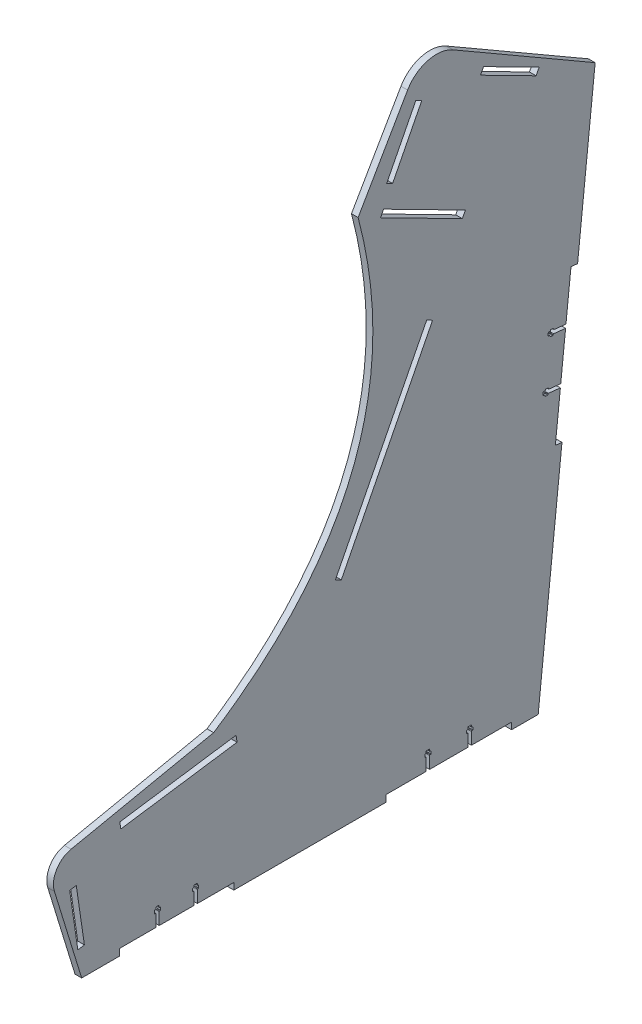
SolidWorks part; units mm, degrees
ref_plane "Front Plane" through (0, 0, 0) normal (0, 0, 1) x (1, 0, 0)
ref_plane "Top Plane" through (0, 0, 0) normal (0, 1, 0) x (1, 0, 0)
ref_plane "Right Plane" through (0, 0, 0) normal (1, 0, 0) x (0, 0, -1)
sketch "Sketch5" plane through (0, 0, 0) normal (1, 0, 0) x (0, 0, -1)
  line L0 (200.2204, 680.0165) -> (997.5537, 680.0165) construction
  line L1 (0, 0) -> (500, 0)
  line L2 (0, 0) -> (0, 800)
  line L3 (0, 800) -> (500, 800)
  line L4 (500, 0) -> (500, 800)
  dimension "D1" = 500
  dimension "D2" = 800
sketch "Sketch6" plane through (0, 0, 0) normal (1, 0, 0) x (0, 0, -1)
  line L0 (443.0084, 0) -> (494.424, 483.6515)
  line L1 (0, 0) -> (500, 0) construction
  line L2 (494.424, 483.6515) -> (366.15, 557.8015)
  line L3 (325.1634, 546.8425) -> (280.507, 469.5903)
  line L5 (150.1347, 132.2032) -> (21.4929, 105.4355)
  line L6 (0, 0) -> (0, 800) construction
  line L7 (6.4499, 79.9789) -> (31.0328, 0)
  line L8 (31.0328, 0) -> (443.0084, 0)
  arc A0 (366.15, 557.8015) -> (325.1634, 546.8425) centre (351.1362, 531.8287) ccw
  arc A1 (21.4929, 105.4355) -> (6.4499, 79.9789) centre (25.5672, 85.8549) ccw
  spline S0 degree 2 poles (280.507, 469.5903) (337.5474, 253.6662) (150.1347, 132.2032) knots 0 0 0 1 1 1
  point P15 (0, 100.9633)
  dimension "D1" = 30
  dimension "D2" = 20
  dimension "D3" = 411.9756
  dimension "D4" = 486.3768
  dimension "D5" = 131.3972
  dimension "D6" = 89.2306
  dimension "D7" = 148.1635
  dimension "D8" = 83.6716
extrude "Boss-Extrude3" add sketch "Sketch6" along normal blind 6
sketch "Sketch7" plane through (6, 0, 0) normal (1, 0, 0) x (0, 0, -1)
  line L0 (27.5611, 23.7476) -> (16.7625, 97.6133)
  line L1 (16.7625, 97.6133) -> (225.0412, 128.062)
  line L2 (225.0412, 128.062) -> (374.5816, 421.6774)
  line L3 (374.5816, 421.6774) -> (295.4085, 462.0008)
  line L4 (295.4085, 462.0008) -> (343.5234, 556.4723)
  line L5 (343.5234, 556.4723) -> (443.8491, 505.3757)
  line L6 (27.5611, 23.7476) -> (33.498, 24.6155)
  line L7 (441.126, 500.0292) -> (346.1469, 548.4027)
  line L8 (346.1469, 548.4027) -> (303.478, 464.6243)
  line L9 (303.478, 464.6243) -> (382.6511, 424.3009)
  line L10 (382.6511, 424.3009) -> (228.9794, 122.574)
  line L11 (228.9794, 122.574) -> (23.5673, 92.5443)
  line L12 (23.5673, 92.5443) -> (33.498, 24.6155)
  line L13 (441.126, 500.0292) -> (443.8491, 505.3757)
  dimension "D1" = 6
  dimension "D2" = 6
  dimension "D3" = 6
  dimension "D4" = 88.8502
  dimension "D5" = 6
  dimension "D6" = 6
  dimension "D7" = 74.6509
  dimension "D8" = 210.4926
  dimension "D9" = 125.307
  dimension "D10" = 6
  dimension "D11" = 106.0184
  dimension "D12" = 112.5881
  dimension "D13" = 335.5032
extrude "Cut-Extrude1" cut sketch "Sketch7" against normal through all
sketch "Sketch9" plane through (6, 0, 0) normal (1, 0, 0) x (0, 0, -1)
  line L0 (16.7625, 97.6133) -> (20.2342, 73.8657)
  line L1 (16.7625, 97.6133) -> (27.5611, 23.7476) construction
  line L2 (20.2342, 73.8657) -> (26.1711, 74.7337)
  line L3 (33.498, 24.6155) -> (23.5673, 92.5443) construction
  line L4 (26.1711, 74.7337) -> (22.6994, 98.4812)
  line L5 (225.0412, 128.062) -> (16.7625, 97.6133) construction
  line L6 (22.6994, 98.4812) -> (16.7625, 97.6133)
  dimension "D1" = 24
extrude "Boss-Extrude10" add sketch "Sketch9" against normal blind 6
sketch "Sketch10" plane through (6, 0, 0) normal (1, 0, 0) x (0, 0, -1)
  line L0 (22.6994, 98.4812) -> (65.4945, 104.7376)
  line L1 (225.0412, 128.062) -> (22.6994, 98.4812) construction
  line L2 (65.4945, 104.7376) -> (66.3624, 98.8007)
  line L3 (23.5673, 92.5443) -> (228.9794, 122.574) construction
  line L4 (66.3624, 98.8007) -> (23.5673, 92.5443)
  line L5 (23.5673, 92.5443) -> (22.6994, 98.4812)
  line L6 (225.0412, 128.062) -> (170.3723, 120.0699)
  line L7 (170.3723, 120.0699) -> (171.2402, 114.133)
  line L8 (171.2402, 114.133) -> (228.9794, 122.574)
  line L9 (228.9794, 122.574) -> (225.0412, 128.062)
  dimension "D1" = 43.25
  dimension "D2" = 55.25
extrude "Boss-Extrude11" add sketch "Sketch10" against normal blind 6
sketch "Sketch11" plane through (6, 0, 0) normal (1, 0, 0) x (0, 0, -1)
  line L0 (382.6511, 424.3009) -> (347.7057, 355.6874)
  line L1 (228.9794, 122.574) -> (382.6511, 424.3009) construction
  line L2 (347.7057, 355.6874) -> (342.3592, 358.4104)
  line L3 (374.5816, 421.6774) -> (225.0412, 128.062) construction
  line L4 (342.3592, 358.4104) -> (377.3046, 427.0239)
  line L5 (382.6511, 424.3009) -> (303.478, 464.6243) construction
  line L6 (377.3046, 427.0239) -> (382.6511, 424.3009)
  line L7 (265.3345, 193.9554) -> (228.9794, 122.574)
  line L8 (228.9794, 122.574) -> (225.0412, 128.062)
  line L9 (225.0412, 128.062) -> (259.988, 196.6784)
  line L10 (259.988, 196.6784) -> (265.3345, 193.9554)
  dimension "D1" = 77
  dimension "D2" = 181.5
extrude "Boss-Extrude12" add sketch "Sketch11" against normal blind 6
sketch "Sketch12" plane through (6, 0, 0) normal (1, 0, 0) x (0, 0, -1)
  line L0 (295.4085, 462.0008) -> (306.3006, 483.3869)
  line L1 (343.5234, 556.4723) -> (295.4085, 462.0008) construction
  line L2 (306.3006, 483.3869) -> (311.6471, 480.6639)
  line L3 (303.478, 464.6243) -> (346.1469, 548.4027) construction
  line L4 (311.6471, 480.6639) -> (300.755, 459.2778)
  line L5 (295.4085, 462.0008) -> (374.5816, 421.6774) construction
  line L6 (300.755, 459.2778) -> (295.4085, 462.0008)
  line L7 (343.5234, 556.4723) -> (332.6314, 535.0862)
  line L8 (332.6314, 535.0862) -> (337.9779, 532.3632)
  line L9 (337.9779, 532.3632) -> (346.1469, 548.4027)
  line L10 (346.1469, 548.4027) -> (390.9685, 525.5748)
  line L11 (346.1469, 548.4027) -> (441.126, 500.0292) construction
  line L12 (390.9685, 525.5748) -> (393.6915, 530.9213)
  line L13 (443.8491, 505.3757) -> (343.5234, 556.4723) construction
  line L14 (393.6915, 530.9213) -> (343.5234, 556.4723)
  dimension "D1" = 24
  dimension "D2" = 24
  dimension "D3" = 56.3
extrude "Boss-Extrude13" add sketch "Sketch12" against normal blind 6
sketch "Sketch13" plane through (6, 0, 0) normal (1, 0, 0) x (0, 0, -1)
  line L0 (0, 0) -> (500, 0) construction
  line L1 (419.0084, 0) -> (305.6784, 0)
  line L2 (419.0084, 0) -> (419.0084, 6)
  line L3 (419.0084, 6) -> (305.6784, 6)
  line L4 (305.6784, 0) -> (305.6784, 6)
  line L6 (65.0217, 0) -> (168.3517, 0)
  line L7 (65.0217, 0) -> (65.0217, 6)
  line L8 (65.0217, 6) -> (168.3517, 6)
  line L9 (168.3517, 0) -> (168.3517, 6)
  dimension "D1" = 6
  dimension "D2" = 6
  dimension "D3" = 113.33
  dimension "D4" = 24
  dimension "D5" = 137.3267
  dimension "D6" = 103.33
  dimension "D7" = 33.9889
extrude "Cut-Extrude2" cut sketch "Sketch13" against normal blind 12
sketch "Sketch15" plane through (6, 0, 0) normal (1, 0, 0) x (0, 0, -1)
  line L0 (464.4724, 201.9057) -> (458.506, 202.54)
  line L1 (443.0084, 0) -> (494.424, 483.6515) construction
  line L2 (458.506, 202.54) -> (472.6009, 335.1263)
  line L3 (472.6009, 335.1263) -> (478.5673, 334.492)
  line L4 (478.5673, 334.492) -> (464.4724, 201.9057)
  dimension "D1" = 6
  dimension "D2" = 133.3333
  dimension "D3" = 150
extrude "Cut-Extrude4" cut sketch "Sketch15" against normal blind 12
sketch "Sketch16" plane through (6, 0, 0) normal (1, 0, 0) x (0, 0, -1)
  line L52 (168.3517, 6) -> (65.0217, 6) construction
  line L53 (97.915, 6) -> (101.015, 6)
  line L54 (97.915, 6) -> (97.915, 22)
  line L55 (97.915, 22) -> (101.015, 22)
  line L56 (101.015, 6) -> (101.015, 22)
  line L57 (65.0217, 6) -> (65.0217, 0) construction
  line L58 (132.3584, 6) -> (135.4584, 6)
  line L59 (132.3584, 6) -> (132.3584, 22)
  line L60 (132.3584, 22) -> (135.4584, 22)
  line L61 (135.4584, 6) -> (135.4584, 22)
  line L62 (168.3517, 0) -> (168.3517, 6) construction
  line L63 (419.0084, 6) -> (305.6784, 6) construction
  line L64 (341.905, 6) -> (345.005, 6)
  line L65 (341.905, 6) -> (341.905, 22)
  line L66 (341.905, 22) -> (345.005, 22)
  line L67 (345.005, 6) -> (345.005, 22)
  line L68 (305.6784, 6) -> (305.6784, 0) construction
  line L69 (379.6817, 6) -> (382.7817, 6)
  line L70 (379.6817, 6) -> (379.6817, 22)
  line L71 (379.6817, 22) -> (382.7817, 22)
  line L72 (382.7817, 6) -> (382.7817, 22)
  line L73 (419.0084, 0) -> (419.0084, 6) construction
  line L74 (463.0403, 245.193) -> (463.368, 248.2756)
  line L75 (472.6009, 335.1263) -> (458.506, 202.54) construction
  line L76 (463.368, 248.2756) -> (447.4577, 249.967)
  line L77 (447.4577, 249.967) -> (447.13, 246.8844)
  line L78 (447.13, 246.8844) -> (463.0403, 245.193)
  line L79 (467.7389, 289.3906) -> (468.0666, 292.4733)
  line L80 (468.0666, 292.4733) -> (452.1562, 294.1646)
  line L81 (452.1562, 294.1646) -> (451.8285, 291.082)
  line L82 (451.8285, 291.082) -> (467.7389, 289.3906)
  line L83 (478.5673, 334.492) -> (472.6009, 335.1263) construction
  line L84 (458.506, 202.54) -> (464.4724, 201.9057) construction
  point P12 (343.455, 6)
  point P15 (381.2317, 6)
  point P38 (99.465, 6)
  point P41 (133.9084, 6)
  point P44 (467.9027, 290.9319)
  point P47 (463.2042, 246.7343)
  dimension "D1" = 3.1
  dimension "D2" = 3.1
  dimension "D3" = 3.1
  dimension "D4" = 3.1
  dimension "D5" = 16
  dimension "D6" = 16
  dimension "D7" = 34.4433
  dimension "D8" = 34.4433
  dimension "D9" = 37.7767
  dimension "D10" = 37.7767
  dimension "D11" = 16
  dimension "D12" = 16
  dimension "D13" = 16
  dimension "D14" = 3.1
  dimension "D15" = 44.4433
  dimension "D16" = 44.4433
extrude "Cut-Extrude5" cut sketch "Sketch16" against normal through all
sketch "Sketch17" plane through (6, 0, 0) normal (1, 0, 0) x (0, 0, -1)
  line L0 (382.7817, 22) -> (379.6817, 22) construction
  line L1 (378.4817, 17.2) -> (383.9817, 17.2)
  line L2 (378.4817, 17.2) -> (378.4817, 20)
  line L3 (378.4817, 20) -> (383.9817, 20)
  line L4 (383.9817, 17.2) -> (383.9817, 20)
  line L5 (345.005, 22) -> (341.905, 22) construction
  line L6 (346.205, 20) -> (340.705, 20)
  line L7 (346.205, 20) -> (346.205, 17.2)
  line L8 (346.205, 17.2) -> (340.705, 17.2)
  line L9 (340.705, 20) -> (340.705, 17.2)
  line L10 (101.015, 22) -> (97.915, 22) construction
  line L11 (136.6584, 20) -> (131.1584, 20)
  line L12 (136.6584, 20) -> (136.6584, 17.2)
  line L13 (136.6584, 17.2) -> (131.1584, 17.2)
  line L14 (131.1584, 20) -> (131.1584, 17.2)
  line L15 (102.215, 20) -> (96.715, 20)
  line L16 (102.215, 20) -> (102.215, 17.2)
  line L17 (102.215, 17.2) -> (96.715, 17.2)
  line L18 (96.715, 20) -> (96.715, 17.2)
  line L19 (135.4584, 22) -> (132.3584, 22) construction
  line L20 (449.5733, 250.9489) -> (452.3576, 250.6529)
  line L21 (452.3576, 250.6529) -> (451.7762, 245.1837)
  line L22 (451.7762, 245.1837) -> (448.9919, 245.4797)
  line L23 (448.9919, 245.4797) -> (449.5733, 250.9489)
  line L24 (463.368, 248.2756) -> (447.4577, 249.967) construction
  line L25 (447.4577, 249.967) -> (447.13, 246.8844) construction
  line L26 (447.13, 246.8844) -> (463.0403, 245.193) construction
  line L27 (454.2719, 295.1465) -> (457.0562, 294.8505)
  line L28 (457.0562, 294.8505) -> (456.4748, 289.3813)
  line L29 (456.4748, 289.3813) -> (453.6904, 289.6773)
  line L30 (453.6904, 289.6773) -> (454.2719, 295.1465)
  line L31 (452.1562, 294.1646) -> (451.8285, 291.082) construction
  line L32 (468.0666, 292.4733) -> (452.1562, 294.1646) construction
  point P6 (381.2317, 20)
  point P7 (381.2317, 22)
  point P14 (343.455, 20)
  point P15 (343.455, 22)
  point P28 (99.465, 20)
  point P29 (99.465, 22)
  point P30 (133.9084, 20)
  point P31 (133.9084, 22)
  dimension "D1" = 2
  dimension "D2" = 2.8
  dimension "D3" = 5.5
  dimension "D4" = 5.5
  dimension "D5" = 2.8
  dimension "D6" = 2
  dimension "D7" = 5.5
  dimension "D8" = 2.8
  dimension "D9" = 2.8
  dimension "D10" = 5.5
  dimension "D11" = 2
  dimension "D12" = 2
  dimension "D13" = 5.5
  dimension "D14" = 2.8
  dimension "D15" = 2
  dimension "D16" = 1.2
  dimension "D17" = 5.5
  dimension "D18" = 2.8
  dimension "D19" = 2
  dimension "D20" = 1.2
extrude "Cut-Extrude6" cut sketch "Sketch17" against normal through all
fillet "Fillet1" radius 0.4 60 edges at (3, 293.6572, -456.9293) (3, 294.8505, -457.0562) (3, 295.1465, -454.2719) (3, 293.9532, -454.145) (3, 294.1646, -452.1562) (3, 291.082, -451.8285) (3, 290.8706, -453.8173) (3, 289.6773, -453.6904) (3, 289.3813, -456.4748) (3, 290.5746, -456.6016) (3, 249.4596, -452.2308) (3, 250.6529, -452.3576) (3, 250.9489, -449.5733) (3, 249.7556, -449.4465) (3, 249.967, -447.4577) (3, 246.8844, -447.13) (3, 246.673, -449.1188) (3, 245.4797, -448.9919) (3, 245.1837, -451.7762) (3, 246.377, -451.9031) (3, 17.2, -382.7817) (3, 17.2, -383.9817) (3, 20, -383.9817) (3, 20, -382.7817) (3, 22, -382.7817) (3, 22, -379.6817) (3, 20, -379.6817) (3, 20, -378.4817) (3, 17.2, -378.4817) (3, 17.2, -379.6817) (3, 17.2, -345.005) (3, 17.2, -346.205) (3, 20, -346.205) (3, 20, -345.005) (3, 22, -345.005) (3, 22, -341.905) (3, 20, -341.905) (3, 20, -340.705) (3, 17.2, -340.705) (3, 17.2, -341.905) (3, 17.2, -135.4584) (3, 17.2, -136.6584) (3, 20, -136.6584) (3, 20, -135.4584) (3, 22, -135.4584) (3, 22, -132.3584) (3, 20, -132.3584) (3, 20, -131.1584) (3, 17.2, -131.1584) (3, 17.2, -132.3584) (3, 17.2, -102.215) (3, 20, -102.215) (3, 22, -101.015) (3, 20, -101.015) (3, 22, -97.915) (3, 20, -96.715) (3, 17.2, -101.015) (3, 20, -97.915) (3, 17.2, -96.715) (3, 17.2, -97.915)
